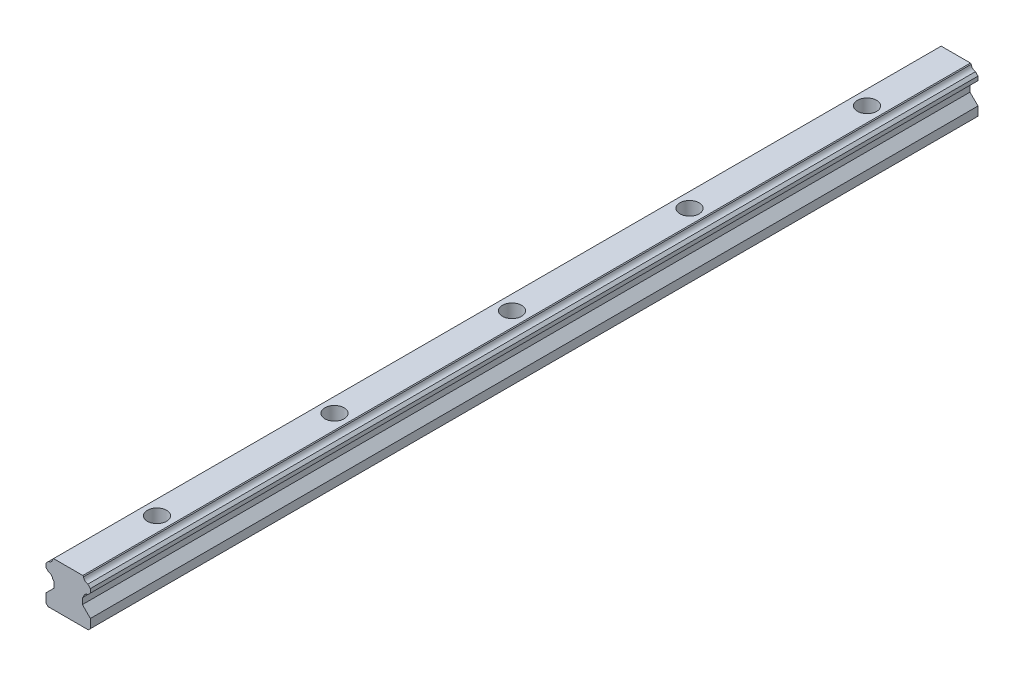
SolidWorks part; units mm, degrees
material "1.4401 (X5CrNiMo17-12-2)"
ref_plane "Спереди" through (0, 0, 0) normal (0, 0, 1) x (1, 0, 0)
ref_plane "Сверху" through (0, 0, 0) normal (0, 1, 0) x (1, 0, 0)
ref_plane "Справа" through (0, 0, 0) normal (1, 0, 0) x (0, 0, -1)
sketch "Model" plane through (0, 0, 0) normal (0, 0, 1) x (1, 0, 0)
  line L7 (6.8, 0) -> (7.5, 0.7)
  line L8 (7.5, 0.7) -> (7.5, 3.6994)
  line L9 (7.5, 3.6994) -> (4.7998, 6.3996)
  line L10 (4.7998, 6.3996) -> (4.7998, 8.4091)
  line L11 (4.7998, 8.4091) -> (5.2008, 8.8101)
  line L12 (6.6481, 10.2574) -> (7.5, 11.1093)
  line L13 (7.5, 11.1093) -> (7.5, 12.4495)
  line L14 (7.5, 12.4495) -> (6.6345, 13.315)
  line L15 (5.2023, 14.7472) -> (4.9495, 15)
  line L16 (4.9495, 15) -> (-4.9495, 15)
  line L17 (-4.9495, 15) -> (-5.2023, 14.7472)
  line L18 (-6.6345, 13.315) -> (-7.5, 12.4495)
  line L19 (-7.5, 12.4495) -> (-7.5, 11.1093)
  line L20 (-7.5, 11.1093) -> (-6.6481, 10.2574)
  line L21 (-5.2008, 8.8101) -> (-4.7998, 8.4091)
  line L22 (-4.7998, 8.4091) -> (-4.7998, 6.3996)
  line L23 (-4.7998, 6.3996) -> (-7.5, 3.6994)
  line L24 (-7.5, 3.6994) -> (-7.5, 0.7)
  line L25 (-7.5, 0.7) -> (-6.8, 0)
  line L26 (-6.8, 0) -> (6.8, 0)
  arc A0 (6.6481, 10.2574) -> (5.2008, 8.8101) centre (6.8215, 8.6367) ccw
  arc A1 (5.2023, 14.7472) -> (6.6345, 13.315) centre (6.8215, 14.9342) ccw
  arc A2 (-6.6345, 13.315) -> (-5.2023, 14.7472) centre (-6.8215, 14.9342) ccw
  arc A3 (-5.2008, 8.8101) -> (-6.6481, 10.2574) centre (-6.8215, 8.6367) ccw
extrude "Бобышка-Вытянуть1" add sketch "Model" along normal blind 300
sketch "Эскиз2" plane through (0, 15, 0) normal (0, 1, 0) x (1, 0, 0)
  line L0 (0, 43.9966) -> (0, -648.9514) construction
  line L1 (4.9495, 0) -> (-4.9495, 0) construction
  circle A0 centre (0, -30) radius 3.25
  circle A1 centre (0, -90) radius 3.25
  circle A2 centre (0, -150) radius 3.25
  circle A3 centre (0, -210) radius 3.25
  circle A4 centre (0, -270) radius 3.25
  circle A5 centre (0, -330) radius 3.25
  circle A6 centre (0, -390) radius 3.25
  circle A7 centre (0, -450) radius 3.25
  circle A8 centre (0, -510) radius 3.25
  circle A9 centre (0, -570) radius 3.25
  dimension "D1" = 10
  dimension "D2" = 30
extrude "Вырез-Вытянуть1" cut sketch "Эскиз2" against normal blind 5.3
sketch "Эскиз3" plane through (0, 9.7, 0) normal (0, 1, 0) x (1, 0, 0)
  circle A0 centre (0, -30) radius 2.25
  circle A1 centre (0, -90) radius 2.25
  circle A2 centre (0, -150) radius 2.25
  circle A3 centre (0, -210) radius 2.25
  circle A4 centre (0, -270) radius 2.25
  circle A5 centre (0, -330) radius 2.25
  circle A6 centre (0, -390) radius 2.25
  circle A7 centre (0, -450) radius 2.25
  circle A8 centre (0, -510) radius 2.25
  circle A9 centre (0, -570) radius 2.25
  dimension "D1" = 10
extrude "Вырез-Вытянуть2" cut sketch "Эскиз3" against normal through all
